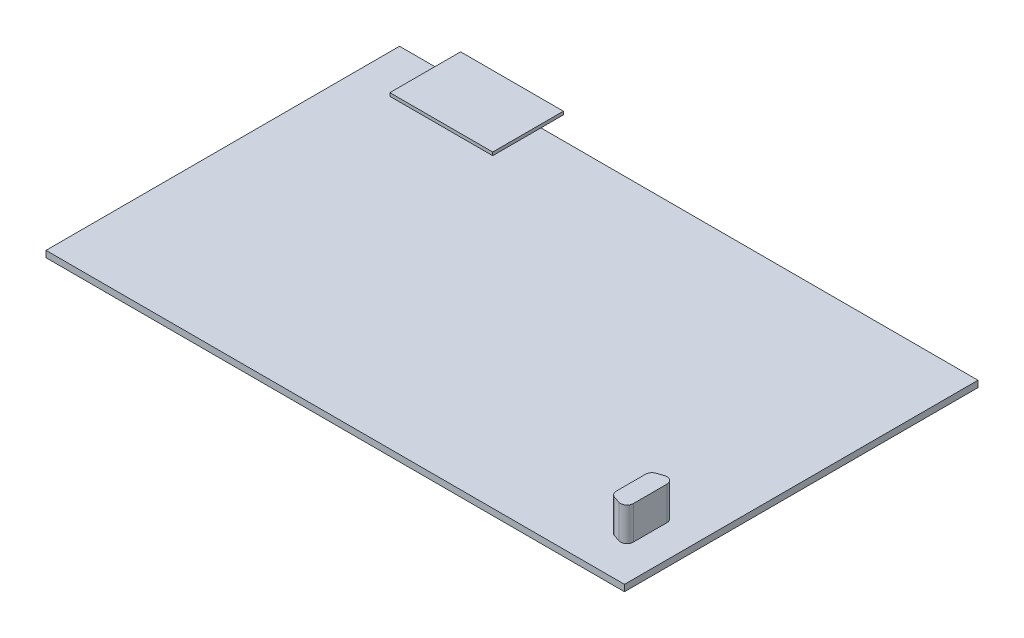
SolidWorks part; units mm, degrees
ref_plane "Front Plane" through (0, 0, 0) normal (0, 0, 1) x (1, 0, 0)
ref_plane "Top Plane" through (0, 0, 0) normal (0, 1, 0) x (1, 0, 0)
ref_plane "Right Plane" through (0, 0, 0) normal (1, 0, 0) x (0, 0, -1)
sketch "Sketch4" plane through (0, 0, 0) normal (0, 1, 0) x (1, 0, 0)
  line L1 (19.05, 158.75) -> (247.65, 158.75)
  line L2 (19.05, 158.75) -> (19.05, 19.05)
  line L3 (19.05, 19.05) -> (247.65, 19.05)
  line L4 (247.65, 158.75) -> (247.65, 19.05)
  dimension "D1" = 19.05
  dimension "D2" = 19.05
  dimension "D3" = 247.65
  dimension "D4" = 158.75
extrude "Boss-Extrude3" add sketch "Sketch4" along normal blind 2.54
sketch "Sketch5" plane through (0, 2.54, 0) normal (0, 1, 0) x (1, 0, 0)
  line L0 (247.65, 158.75) -> (19.05, 158.75) construction
  line L1 (40.64, 148.59) -> (73.66, 148.59)
  line L2 (40.64, 148.59) -> (40.64, 143.51)
  line L3 (40.64, 143.51) -> (73.66, 143.51)
  line L4 (73.66, 148.59) -> (73.66, 143.51)
  line L5 (19.05, 158.75) -> (19.05, 19.05) construction
  dimension "D1" = 33.02
  dimension "D2" = 5.08
  dimension "D3" = 10.16
  dimension "D4" = 21.59
extrude "Boss-Extrude4" add sketch "Sketch5" along normal blind 2.54
sketch "Sketch6" plane through (0, 5.08, 0) normal (0, 1, 0) x (1, 0, 0)
  line L1 (36.83, 165.1) -> (77.47, 165.1)
  line L2 (36.83, 165.1) -> (36.83, 137.16)
  line L3 (36.83, 137.16) -> (77.47, 137.16)
  line L4 (77.47, 165.1) -> (77.47, 137.16)
  line L5 (73.66, 148.59) -> (40.64, 148.59) construction
  line L6 (73.66, 143.51) -> (73.66, 148.59) construction
  dimension "D1" = 27.94
  dimension "D2" = 40.64
  dimension "D3" = 11.43
  dimension "D4" = 3.81
extrude "Boss-Extrude5" add sketch "Sketch6" along normal blind 1.27
sketch "Sketch8" plane through (0, 2.54, 0) normal (0, 1, 0) x (1, 0, 0)
  line L0 (227.33, 49.53) -> (234.95, 52.07)
  line L1 (234.95, 52.07) -> (234.95, 31.75)
  line L2 (234.95, 31.75) -> (227.33, 34.29)
  line L3 (227.33, 34.29) -> (227.33, 49.53)
  line L4 (247.65, 19.05) -> (247.65, 158.75) construction
  line L5 (19.05, 19.05) -> (247.65, 19.05) construction
  dimension "D1" = 20.32
  dimension "D2" = 15.24
  dimension "D3" = 7.62
  dimension "D4" = 2.54
  dimension "D5" = 12.7
  dimension "D6" = 12.7
extrude "Boss-Extrude7" add sketch "Sketch8" along normal blind 13.208
fillet "Fillet1" radius 2.54 4 edges at (227.33, 9.144, -49.53) (234.95, 9.144, -52.07) (227.33, 9.144, -34.29) (234.95, 9.144, -31.75)
